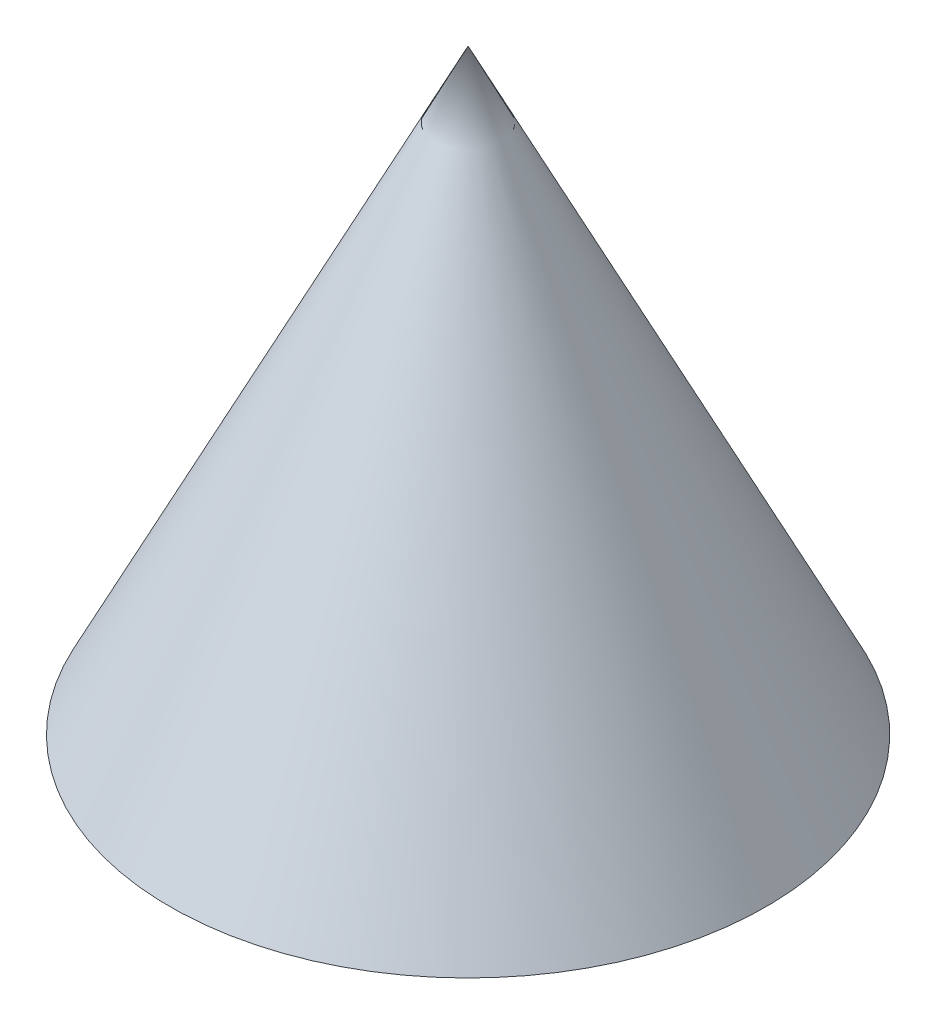
SolidWorks part; units mm, degrees
ref_plane "Front Plane" through (0, 0, 0) normal (0, 0, 1) x (1, 0, 0)
ref_plane "Top Plane" through (0, 0, 0) normal (0, 1, 0) x (1, 0, 0)
ref_plane "Right Plane" through (0, 0, 0) normal (1, 0, 0) x (0, 0, -1)
sketch "Sketch1" plane through (0, 0, 0) normal (0, 0, 1) x (1, 0, 0)
  line L0 (0, 0) -> (0, 254)
  line L1 (0, 254) -> (127, 0)
  line L2 (127, 0) -> (0, 0)
  dimension "D1" = 254
  dimension "D2" = 127
revolve "Revolve1" add sketch "Sketch1" angle 360 about L0
